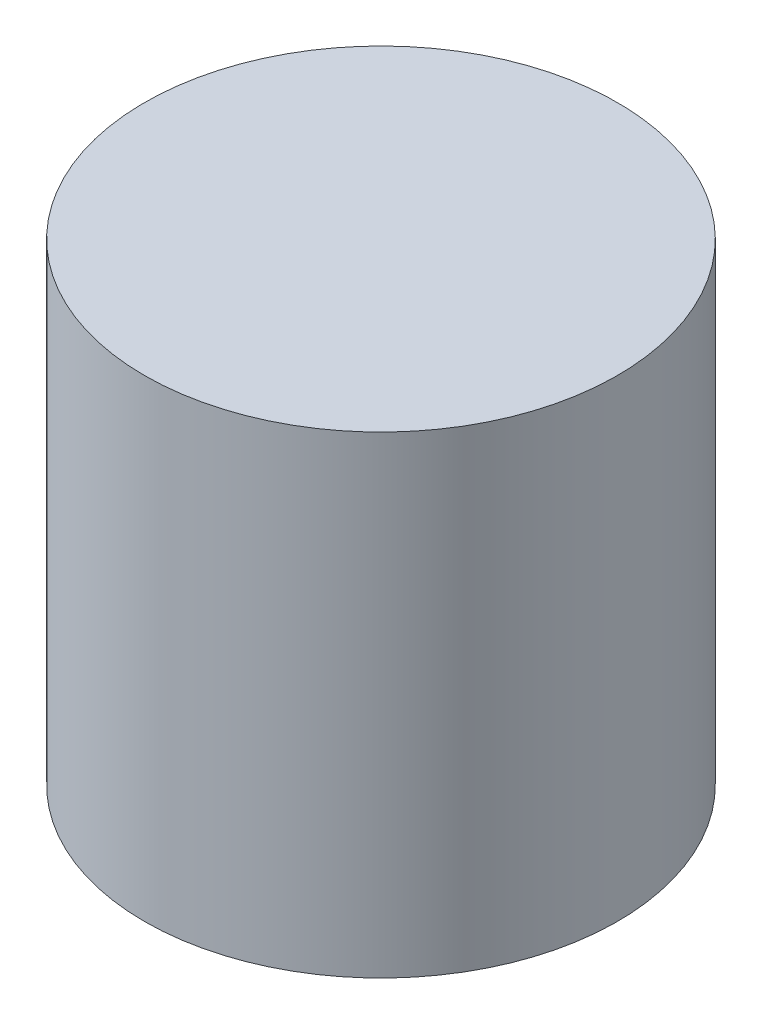
SolidWorks part; units mm, degrees
ref_plane "Front Plane" through (0, 0, 0) normal (0, 0, 1) x (1, 0, 0)
ref_plane "Top Plane" through (0, 0, 0) normal (0, 1, 0) x (1, 0, 0)
ref_plane "Right Plane" through (0, 0, 0) normal (1, 0, 0) x (0, 0, -1)
sketch "Sketch1" plane through (0, 0, 0) normal (0, 1, 0) x (1, 0, 0)
  circle A0 centre (0, 0) radius 1.27
  dimension "D1" = 2.54
extrude "Boss-Extrude1" add sketch "Sketch1" along normal blind 2.54
